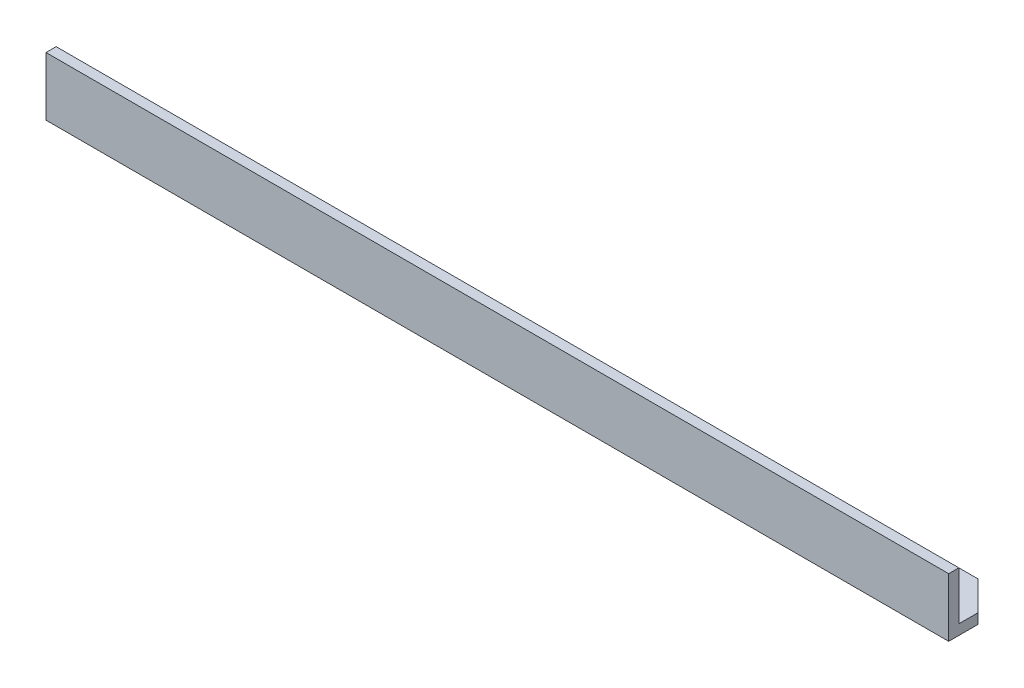
SolidWorks part; units mm, degrees
ref_plane "Front Plane" through (0, 0, 0) normal (0, 0, 1) x (1, 0, 0)
ref_plane "Top Plane" through (0, 0, 0) normal (0, 1, 0) x (1, 0, 0)
ref_plane "Right Plane" through (0, 0, 0) normal (1, 0, 0) x (0, 0, -1)
sketch "Sketch1" plane through (0, 0, 0) normal (1, 0, 0) x (0, 0, -1)
  line L0 (0, 0) -> (20, 0)
  line L1 (20, 0) -> (20, 3.4612)
  line L2 (20, 3.4612) -> (3.4612, 3.4612)
  line L3 (3.4612, 3.4612) -> (3.4612, 20)
  line L4 (3.4612, 20) -> (0, 20)
  line L5 (0, 20) -> (0, 0)
  dimension "D1" = 3.4612
  dimension "D2" = 20
extrude "Boss-Extrude1" add sketch "Sketch1" along normal blind 308
sketch "Sketch2" plane through (0, 0, 0) normal (0, 1, 0) x (1, 0, 0)
  line L1 (308, 0) -> (0, 0) construction
  line L2 (308, 20) -> (308, 3.4612) construction
  line L3 (308, 10) -> (298, 20)
  line L4 (308, 20) -> (0, 20) construction
  line L5 (298, 20) -> (308, 20)
  line L6 (308, 20) -> (308, 10)
  line L7 (0, 20) -> (5, 20)
  line L8 (5, 20) -> (0, 15)
  line L10 (0, 15) -> (0, 20)
  circle A0 centre (278, 15.25) radius 3
  point P18 (0, 0)
  dimension "D1" = 6
  dimension "D2" = 30
  dimension "D3" = 15.25
  dimension "D4" = 10
  dimension "D5" = 5
extrude "Cut-Extrude1" cut sketch "Sketch2" along normal through all
